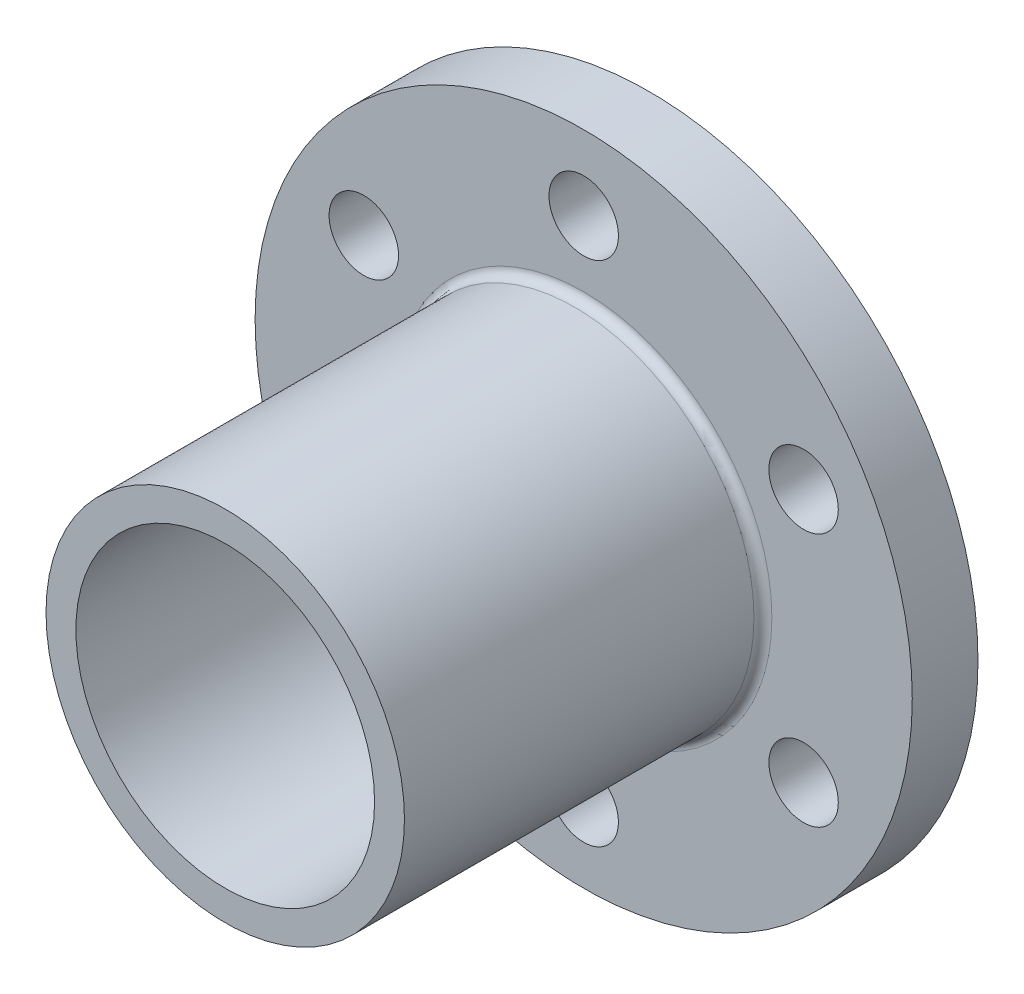
SolidWorks part; units mm, degrees
ref_plane "Front Plane" through (0, 0, 0) normal (0, 0, 1) x (1, 0, 0)
ref_plane "Top Plane" through (0, 0, 0) normal (0, 1, 0) x (1, 0, 0)
ref_plane "Right Plane" through (0, 0, 0) normal (1, 0, 0) x (0, 0, -1)
sketch "Sketch1" plane through (0, 0, 0) normal (0, 0, 1) x (1, 0, 0)
  circle A0 centre (0, 0) radius 110
  dimension "D1" = 220
extrude "Boss-Extrude1" add sketch "Sketch1" along normal blind 22
sketch "Sketch2" plane through (0, 0, 22) normal (0, 0, 1) x (1, 0, 0)
  circle A0 centre (0, 0) radius 60
  dimension "D1" = 120
extrude "Boss-Extrude2" add sketch "Sketch2" along normal blind 120
sketch "Sketch3" plane through (0, 0, 142) normal (0, 0, 1) x (1, 0, 0)
  circle A0 centre (0, 0) radius 50
  dimension "D1" = 100
extrude "Cut-Extrude1" cut sketch "Sketch3" against normal through all
sketch "Sketch4" plane through (0, 0, 22) normal (0, 0, 1) x (1, 0, 0)
  circle A0 centre (0, 85) radius 11.6234
  circle A1 centre (73.6122, 42.5) radius 11.6234
  circle A2 centre (73.6122, -42.5) radius 11.6234
  circle A3 centre (0, -85) radius 11.6234
  circle A4 centre (-73.6122, -42.5) radius 11.6234
  circle A5 centre (-73.6122, 42.5) radius 11.6234
  point P15 (0, 0)
  dimension "D1" = 23.2469
  dimension "D2" = 85
  dimension "D3" = 6
extrude "Cut-Extrude2" cut sketch "Sketch4" against normal through all
fillet "Fillet1" radius 3 1 edges at (60, 0, 22)
